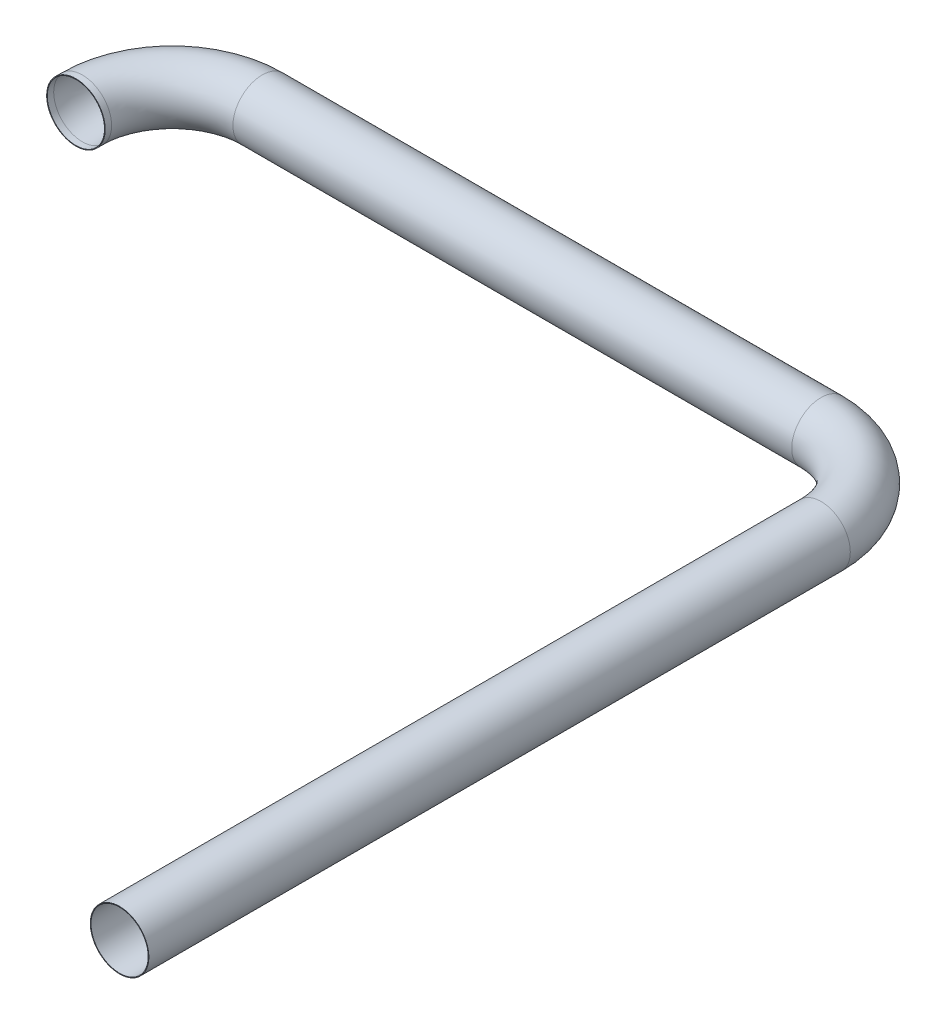
SolidWorks part; units mm, degrees
ref_plane "Front Plane" through (0, 0, 0) normal (0, 0, 1) x (1, 0, 0)
ref_plane "Top Plane" through (0, 0, 0) normal (0, 1, 0) x (1, 0, 0)
ref_plane "Right Plane" through (0, 0, 0) normal (1, 0, 0) x (0, 0, -1)
sketch "Sketch1" plane through (0, 0, 0) normal (0, 1, 0) x (1, 0, 0)
  line L0 (0, 0) -> (0, 1092)
  line L1 (-140, 1232) -> (-1010, 1232)
  line L2 (-1150, 1092) -> (-1150, 1082)
  arc A0 (0, 1092) -> (-140, 1232) centre (-140, 1092) ccw
  arc A1 (-1010, 1232) -> (-1150, 1092) centre (-1010, 1092) ccw
  point P6 (0, 1232)
  point P10 (-1150, 1232)
  dimension "D3" = 140
  dimension "D5" = 140
  dimension "D1" = 1232
  dimension "D2" = 1150
  dimension "D4" = 150
sketch "Sketch2" plane through (0, 0, 0) normal (0, 0, 1) x (1, 0, 0)
  circle A0 centre (0, 0) radius 45.59
  circle A1 centre (0, 0) radius 44.59
  dimension "D1" = 91.18
  dimension "D2" = 89.18
sweep "Sweep2" add profiles "Sketch2" path "Sketch1"
